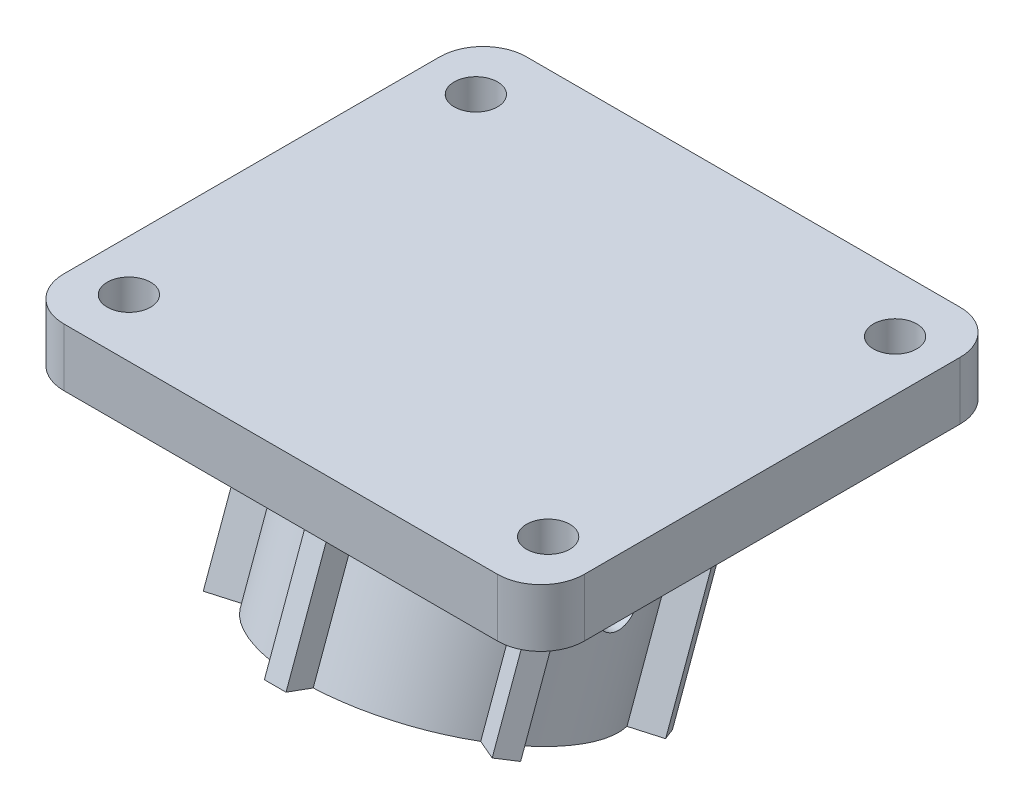
SolidWorks part; units mm, degrees
ref_plane "Ön Düzlem" through (0, 0, 0) normal (0, 0, 1) x (1, 0, 0)
ref_plane "Üst Düzlem" through (0, 0, 0) normal (0, 1, 0) x (1, 0, 0)
ref_plane "Sağ Düzlem" through (0, 0, 0) normal (1, 0, 0) x (0, 0, -1)
sketch "Çizim2" plane through (0, 0, 0) normal (0, 1, 0) x (1, 0, 0)
  line L0 (18, 0) -> (0, 0) construction
  line L1 (15, -16) -> (-15, -16)
  line L2 (18, -13) -> (18, 13)
  line L3 (15, 16) -> (-15, 16)
  line L4 (-18, -13) -> (-18, 13)
  line L5 (18, -16) -> (17.069, -15.1724) construction
  line L6 (18, 16) -> (17.069, 15.1724) construction
  line L7 (0, 16) -> (0, 0) construction
  line L8 (-17.1213, 15.1213) -> (-18, 16) construction
  line L9 (-17.1213, -15.1213) -> (-18, -16) construction
  arc A4 (18, 13) -> (15, 16) centre (15, 13) ccw
  arc A5 (15, -16) -> (18, -13) centre (15, -13) ccw
  arc A6 (-15, -16) -> (-18, -13) centre (-15, -13) cw
  arc A7 (-15, 16) -> (-18, 13) centre (-15, 13) ccw
  circle A9 centre (14.5, -12) radius 1.5
  circle A10 centre (-14.5, -12) radius 1.5
  circle A11 centre (14.5, 12) radius 1.5
  circle A12 centre (-14.5, 12) radius 1.5
  point P0 (0, 0)
  dimension "D5" = 24
  dimension "D6" = 3
  dimension "D3" = 3
  dimension "D1" = 32
  dimension "D2" = 36
  dimension "D4" = 29
  dimension "D7" = 12
  dimension "D8" = 14.5
extrude "Yükseklik-Ekstrüzyon1" add sketch "Çizim2" along normal blind 4
ref_plane "Düzlem1" through (0, 0, 0) normal (-1, 0, 0) x (0, 0, 1)
sketch "Çizim3" plane through (0, 0, 0) normal (-1, 0, 0) x (0, 0, 1)
  line L0 (0, 0) -> (5.1303, -14.0954) construction
  line L1 (-13, 0) -> (13, 0) construction
  dimension "D1" = 70
  dimension "D2" = 15
ref_plane "Düzlem2" through (0, -14.0954, 5.1303) normal (0, -0.9397, 0.342) x (-1, 0, 0)
sketch "Çizim4" plane through (0, -14.0954, 5.1303) normal (0, -0.9397, 0.342) x (-1, 0, 0)
  line L0 (-0.75, 9.9718) -> (-0.75, 11.9718)
  line L1 (-0.75, 11.9718) -> (0.75, 11.9718)
  line L2 (0.75, 11.9718) -> (0.75, 9.9718)
  line L3 (0, 0) -> (0, 10) construction
  line L4 (8.2609, 5.6354) -> (9.9929, 6.6354)
  line L5 (9.9929, 6.6354) -> (10.7429, 5.3364)
  line L6 (10.7429, 5.3364) -> (9.0109, 4.3364)
  line L7 (9.0109, -4.3364) -> (10.7429, -5.3364)
  line L8 (10.7429, -5.3364) -> (9.9929, -6.6354)
  line L9 (9.9929, -6.6354) -> (8.2609, -5.6354)
  line L10 (0.75, -9.9718) -> (0.75, -11.9718)
  line L11 (0.75, -11.9718) -> (-0.75, -11.9718)
  line L12 (-0.75, -11.9718) -> (-0.75, -9.9718)
  line L13 (-8.2609, -5.6354) -> (-9.9929, -6.6354)
  line L14 (-9.9929, -6.6354) -> (-10.7429, -5.3364)
  line L15 (-10.7429, -5.3364) -> (-9.0109, -4.3364)
  line L16 (-9.0109, 4.3364) -> (-10.7429, 5.3364)
  line L17 (-10.7429, 5.3364) -> (-9.9929, 6.6354)
  line L18 (-9.9929, 6.6354) -> (-8.2609, 5.6354)
  circle A0 centre (0, 0) radius 10
  circle A1 centre (0, 0) radius 8
  point P6 (0, 11.9718)
  dimension "D1" = 20
  dimension "D2" = 16
  dimension "D3" = 1.5
  dimension "D4" = 2
  dimension "D5" = 6
extrude "Yükseklik-Ekstrüzyon2" add sketch "Çizim4" against normal up to surface (18.6295 mm away)
sketch "Çizim5" plane through (-18, 0, 0) normal (-1, 0, 0) x (0, 0, 1)
  line L0 (5.1303, -14.0954) -> (0, 0) construction
  line L1 (1.0554, -15.5785) -> (9.2052, -12.6123) construction
  circle A0 centre (2.5652, -7.0477) radius 1.5
  dimension "D1" = 3
extrude "Kes-Ekstrüzyon1" cut sketch "Çizim5" against normal up to surface (27.9002 mm away)
